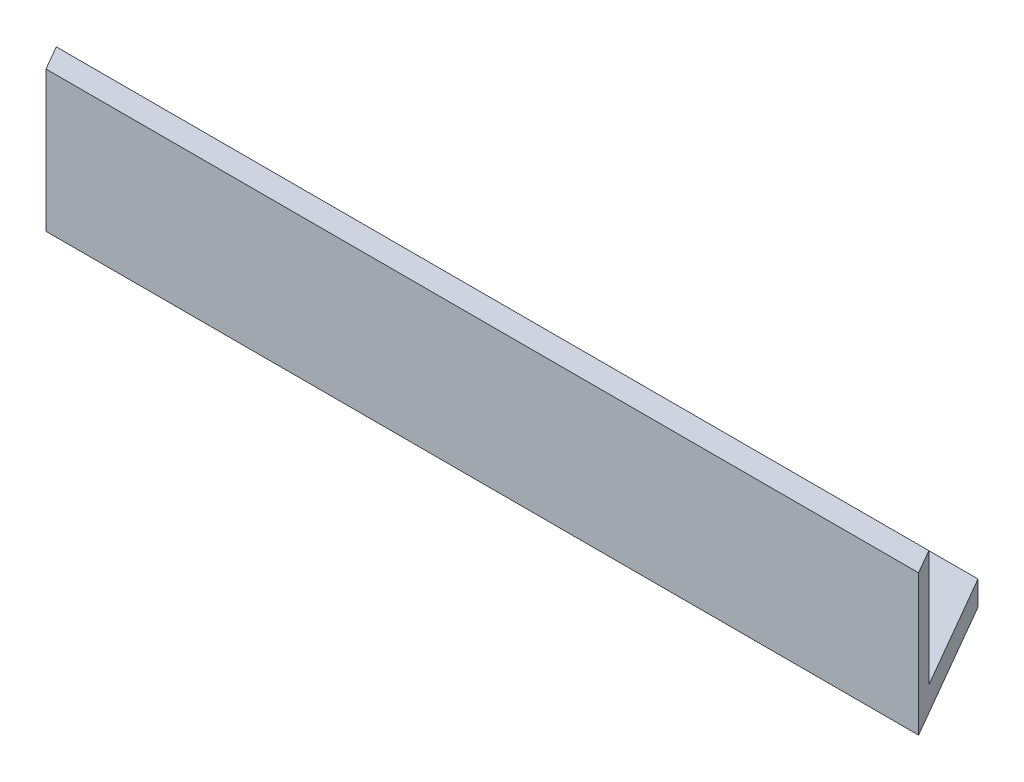
SolidWorks part; units mm, degrees
ref_plane "Front Plane" through (0, 0, 0) normal (0, 0, 1) x (1, 0, 0)
ref_plane "Top Plane" through (0, 0, 0) normal (0, 1, 0) x (1, 0, 0)
ref_plane "Right Plane" through (0, 0, 0) normal (1, 0, 0) x (0, 0, -1)
sketch "Sketch1" plane through (0, 0, 0) normal (1, 0, 0) x (0, 0, -1)
  line L0 (0, 0) -> (20, 0)
  line L1 (20, 0) -> (20, 3.4612)
  line L2 (20, 3.4612) -> (3.4612, 3.4612)
  line L3 (3.4612, 3.4612) -> (3.4612, 20)
  line L4 (3.4612, 20) -> (0, 20)
  line L5 (0, 20) -> (0, 0)
  dimension "D1" = 3.4612
  dimension "D2" = 20
extrude "Boss-Extrude1" add sketch "Sketch1" along normal blind 240
sketch "Sketch2" plane through (0, 0, 0) normal (0, -1, 0) x (1, 0, 0)
  line L1 (240, -20) -> (0, -20) construction
  line L3 (0, -20) -> (0, 0)
  line L4 (240, 0) -> (240, -20)
  line L5 (240, -20) -> (124.1303, -20)
  line L7 (240, 0) -> (0, 0) construction
  line L9 (0, -20) -> (11.547, 0)
  line L10 (11.547, 0) -> (0, 0)
  line L11 (240, 0) -> (135.6773, 0)
  line L12 (135.6773, 0) -> (124.1303, -20)
  dimension "D1" = 30
  dimension "D2" = 107.5
extrude "Cut-Extrude1" cut sketch "Sketch2" against normal through all
